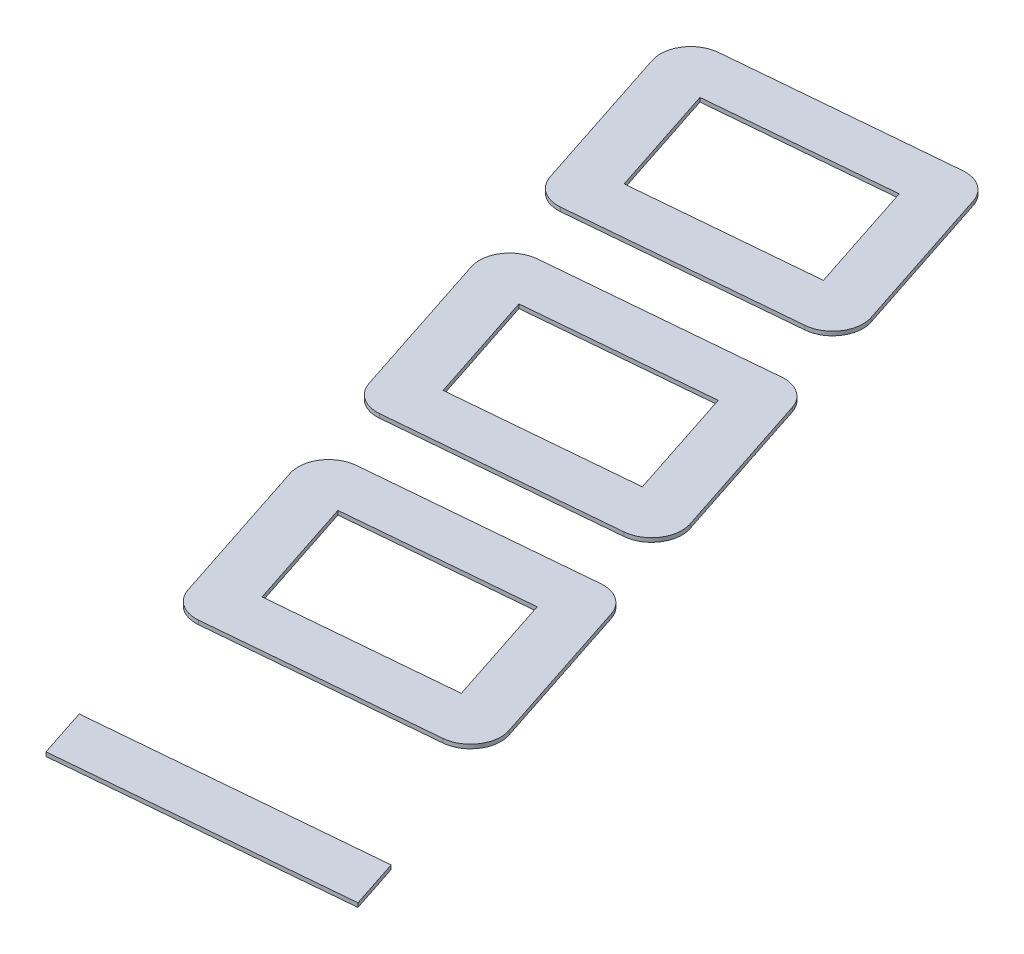
SolidWorks part; units mm, degrees
ref_plane "Front Plane" through (0, 0, 0) normal (0, 0, 1) x (1, 0, 0)
ref_plane "Top Plane" through (0, 0, 0) normal (0, 1, 0) x (1, 0, 0)
ref_plane "Right Plane" through (0, 0, 0) normal (1, 0, 0) x (0, 0, -1)
sketch "Sketch1" plane through (0, 0, 0) normal (0, 1, 0) x (1, 0, 0)
  line L0 (25.4017, -44.9866) -> (26.3489, -47.8755) construction
  line L5 (23.2209, -38.335) -> (24.1681, -41.2239) construction
  line L10 (24.8149, -40.2431) -> (30.3602, -39.7548)
  line L39 (24.1681, -41.2239) -> (25.4017, -44.9866)
  line L56 (26.1802, -45.5) -> (31.7255, -45.0117)
  line L60 (31.1387, -40.2682) -> (32.3724, -44.0309)
  line L61 (25.5521, -41.433) -> (30.0746, -41.0348)
  line L62 (30.0746, -41.0348) -> (30.9883, -43.8218)
  line L64 (26.4659, -44.22) -> (30.9883, -43.8218)
  line L74 (25.5521, -41.433) -> (26.4659, -44.22)
  line L75 (27.5826, -51.6382) -> (28.5298, -54.5271) construction
  line L77 (26.9958, -46.8947) -> (32.5411, -46.4064)
  line L78 (26.3489, -47.8755) -> (27.5826, -51.6382)
  line L83 (28.3611, -52.1516) -> (33.9064, -51.6633)
  line L88 (33.3196, -46.9198) -> (34.5532, -50.6825)
  line L90 (27.733, -48.0846) -> (32.2554, -47.6864)
  line L91 (32.2554, -47.6864) -> (33.1692, -50.4734)
  line L95 (28.6467, -50.8716) -> (33.1692, -50.4734)
  line L96 (27.733, -48.0846) -> (28.6467, -50.8716)
  line L101 (29.1766, -53.5463) -> (34.722, -53.058) construction
  line L104 (28.5298, -54.5271) -> (29.549, -57.6358) construction
  line L144 (29.9138, -54.7362) -> (34.4363, -54.338) construction
  line L146 (22.6341, -33.5915) -> (28.1794, -33.1031)
  line L147 (21.9872, -34.5723) -> (23.2209, -38.335)
  line L148 (23.9993, -38.8484) -> (29.5447, -38.3601)
  line L149 (28.9579, -33.6166) -> (30.1915, -37.3793)
  line L150 (23.3712, -34.7814) -> (27.8937, -34.3831)
  line L151 (27.8937, -34.3831) -> (28.8075, -37.1702)
  line L152 (24.285, -37.5684) -> (28.8075, -37.1702)
  line L153 (23.3712, -34.7814) -> (24.285, -37.5684)
  line L155 (34.4363, -54.338) -> (35.3501, -57.125) construction
  line L173 (29.9138, -54.7362) -> (30.8276, -57.5232) construction
  line L179 (34.722, -53.058) -> (35.8411, -52.9594) construction
  line L182 (28.8922, -55.6325) -> (29.2921, -56.8521)
  line L185 (35.9718, -55.0091) -> (28.8922, -55.6325)
  line L186 (35.9718, -55.0091) -> (36.3717, -56.2287)
  line L187 (36.3717, -56.2287) -> (29.2921, -56.8521)
  line L188 (35.9718, -55.0091) -> (36.3717, -56.2287) construction
  arc A13 (28.9579, -33.6166) -> (28.1794, -33.1031) centre (28.2452, -33.8503) ccw
  arc A14 (30.1915, -37.3793) -> (29.5447, -38.3601) centre (29.4789, -37.613) cw
  arc A15 (23.9993, -38.8484) -> (23.2209, -38.335) centre (23.9336, -38.1013) cw
  arc A16 (21.9872, -34.5723) -> (22.6341, -33.5915) centre (22.6999, -34.3386) cw
  arc A23 (31.1387, -40.2682) -> (30.3602, -39.7548) centre (30.426, -40.5019) ccw
  arc A24 (32.3724, -44.0309) -> (31.7255, -45.0117) centre (31.6597, -44.2646) cw
  arc A25 (26.1802, -45.5) -> (25.4017, -44.9866) centre (26.1144, -44.7529) cw
  arc A26 (24.1681, -41.2239) -> (24.8149, -40.2431) centre (24.8807, -40.9902) cw
  arc A27 (33.3196, -46.9198) -> (32.5411, -46.4064) centre (32.6069, -47.1535) ccw
  arc A28 (34.5532, -50.6825) -> (33.9064, -51.6633) centre (33.8406, -50.9162) cw
  arc A29 (28.3611, -52.1516) -> (27.5826, -51.6382) centre (28.2953, -51.4045) cw
  arc A30 (26.3489, -47.8755) -> (26.9958, -46.8947) centre (27.0616, -47.6418) cw
  arc A31 (35.5004, -53.5714) -> (34.722, -53.058) centre (34.7877, -53.8051) ccw construction
  arc A34 (28.5298, -54.5271) -> (29.1766, -53.5463) centre (29.2424, -54.2934) cw construction
  point P0 (36.1717, -55.6189)
  point P46 (35.5149, -53.6156)
  point P48 (36.1717, -55.6189)
  point P136 (28.7724, -33.0509)
  point P139 (30.4859, -38.2772)
  dimension "D6" = 5.5
extrude "Boss-Extrude1" add sketch "Sketch1" along normal blind 0.1
scale "Scale1" [suppressed]
